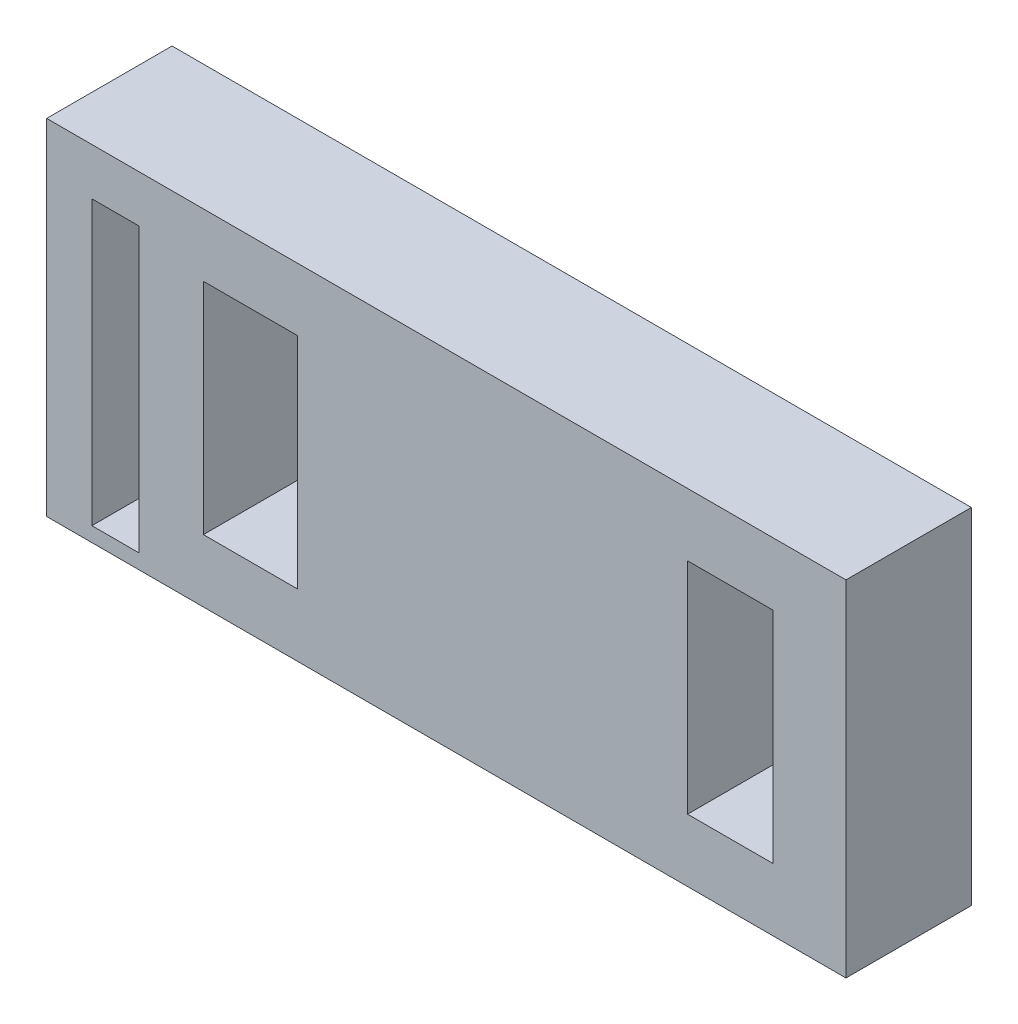
SolidWorks part; units mm, degrees
ref_plane "Front Plane" through (0, 0, 0) normal (0, 0, 1) x (1, 0, 0)
ref_plane "Top Plane" through (0, 0, 0) normal (0, 1, 0) x (1, 0, 0)
ref_plane "Right Plane" through (0, 0, 0) normal (1, 0, 0) x (0, 0, -1)
sketch "Sketch1" plane through (0, 0, 0) normal (0, 0, 1) x (1, 0, 0)
  line L1 (-134.7523, 54.9771) -> (120.2477, 54.9771)
  line L2 (-134.7523, 54.9771) -> (-134.7523, -55.0229)
  line L3 (-134.7523, -55.0229) -> (120.2477, -55.0229)
  line L4 (120.2477, 54.9771) -> (120.2477, -55.0229)
  dimension "D1" = 255
  dimension "D2" = 110
extrude "Boss-Extrude1" add sketch "Sketch1" along normal blind 40
sketch "Sketch2" plane through (0, 0, 40) normal (0, 0, 1) x (1, 0, 0)
  line L0 (-134.7523, 54.9771) -> (-134.7523, -55.0229) construction
  line L1 (-84.7523, 34.9771) -> (-54.7523, 34.9771)
  line L2 (-84.7523, 34.9771) -> (-84.7523, -35.0229)
  line L3 (-84.7523, -35.0229) -> (-54.7523, -35.0229)
  line L4 (-54.7523, 34.9771) -> (-54.7523, -35.0229)
  line L5 (120.2477, 54.9771) -> (-134.7523, 54.9771) construction
  line L6 (-134.7523, -55.0229) -> (120.2477, -55.0229) construction
  line L7 (-120.3303, 39.9771) -> (-105.3303, 39.9771)
  line L8 (-120.3303, 39.9771) -> (-120.3303, -50.3386)
  line L9 (-120.3303, -50.3386) -> (-105.3303, -50.3386)
  line L10 (-105.3303, 39.9771) -> (-105.3303, -50.3386)
  line L11 (69.7166, 34.9771) -> (96.9873, 34.9771)
  line L12 (69.7166, 34.9771) -> (69.7166, -35.0229)
  line L13 (69.7166, -35.0229) -> (96.9873, -35.0229)
  line L14 (96.9873, 34.9771) -> (96.9873, -35.0229)
  dimension "D1" = 70
  dimension "D2" = 30
  dimension "D3" = 50
  dimension "D4" = 20
  dimension "D5" = 15
  dimension "D6" = 15
  dimension "D7" = 20
  dimension "D8" = 20
extrude "Cut-Extrude1" cut sketch "Sketch2" against normal blind 30
